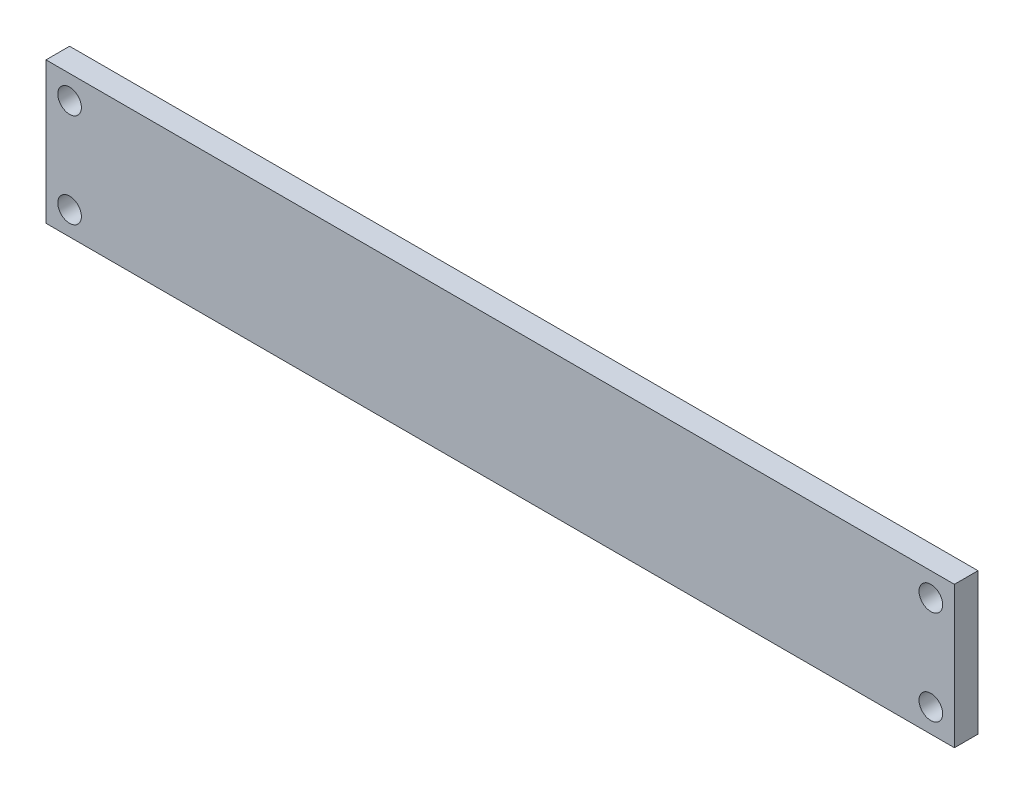
SolidWorks part; units mm, degrees
ref_plane "Płaszczyzna przednia" through (0, 0, 0) normal (0, 0, 1) x (1, 0, 0)
ref_plane "Płaszczyzna górna" through (0, 0, 0) normal (0, 1, 0) x (1, 0, 0)
ref_plane "Płaszczyzna prawa" through (0, 0, 0) normal (1, 0, 0) x (0, 0, -1)
sketch "Szkic1" plane through (0, 0, 0) normal (0, 0, 1) x (1, 0, 0)
  line L1 (-192.5, 30) -> (192.5, 30)
  line L2 (-192.5, 30) -> (-192.5, -30)
  line L3 (-192.5, -30) -> (192.5, -30)
  line L4 (192.5, 30) -> (192.5, -30)
  line L5 (-192.5, 30) -> (192.5, -30) construction
  line L6 (-192.5, -30) -> (192.5, 30) construction
  circle A0 centre (-182.5, 20) radius 5
  circle A2 centre (182.5, 20) radius 5
  circle A3 centre (182.5, -20) radius 5
  circle A4 centre (-182.5, -20) radius 5
  point P0 (0, 0)
  dimension "D5" = 10
  dimension "D1" = 60
  dimension "D2" = 385
  dimension "D3" = 10
  dimension "D4" = 10
  dimension "D6" = 2
  dimension "D7" = 2
extrude "Dodanie-wyciągnięcie1" add sketch "Szkic1" along normal blind 10
